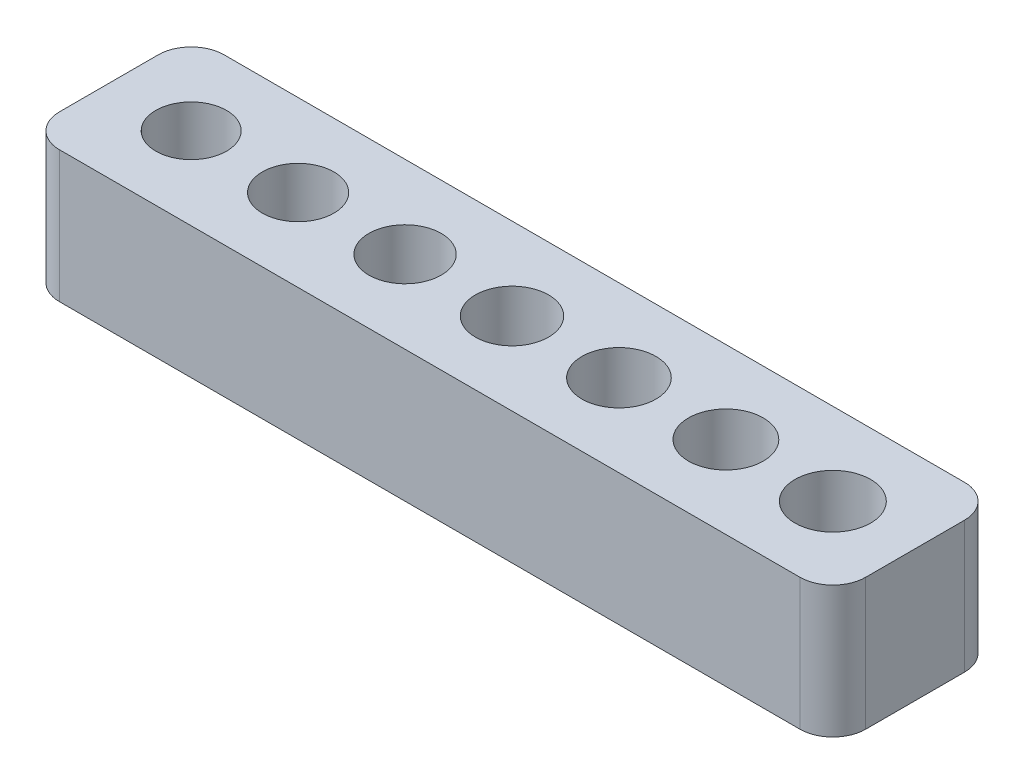
SolidWorks part; units mm, degrees
ref_plane "Front Plane" through (0, 0, 0) normal (0, 0, 1) x (1, 0, 0)
ref_plane "Top Plane" through (0, 0, 0) normal (0, 1, 0) x (1, 0, 0)
ref_plane "Right Plane" through (0, 0, 0) normal (1, 0, 0) x (0, 0, -1)
sketch "Sketch1" plane through (0, 0, 0) normal (0, 1, 0) x (1, 0, 0)
  line L0 (5, 5) -> (44, 5) construction
  line L1 (0, 0) -> (49, 0)
  line L2 (0, 0) -> (0, 10)
  line L3 (0, 10) -> (49, 10)
  line L4 (49, 0) -> (49, 10)
  circle A0 centre (5, 5) radius 2.15
  circle A1 centre (11.5, 5) radius 2.175
  circle A2 centre (18, 5) radius 2.2
  circle A3 centre (24.5, 5) radius 2.225
  circle A4 centre (44, 5) radius 2.3
  circle A10 centre (31, 5) radius 2.25
  circle A11 centre (37.5, 5) radius 2.275
  point P8 (36.8457, 3.5)
  dimension "D1" = 4.3
  dimension "D2" = 4.35
  dimension "D3" = 4.4
  dimension "D4" = 4.45
  dimension "D5" = 4.6
  dimension "D6" = 6.5
  dimension "D7" = 6.5
  dimension "D8" = 6.5
  dimension "D9" = 4.5
  dimension "D10" = 4.55
  dimension "D13" = 6.5
  dimension "D14" = 6.5
  dimension "D15" = 6.5
  dimension "D16" = 5
  dimension "D18" = 5
  dimension "D11" = 5
  dimension "D12" = 5
  dimension "D17" = 5
extrude "Boss-Extrude1" add sketch "Sketch1" along normal blind 8
fillet "Fillet1" radius 2 4 edges at (0, 4, -10) (49, 4, -10) (0, 4, 0) (49, 4, 0)
